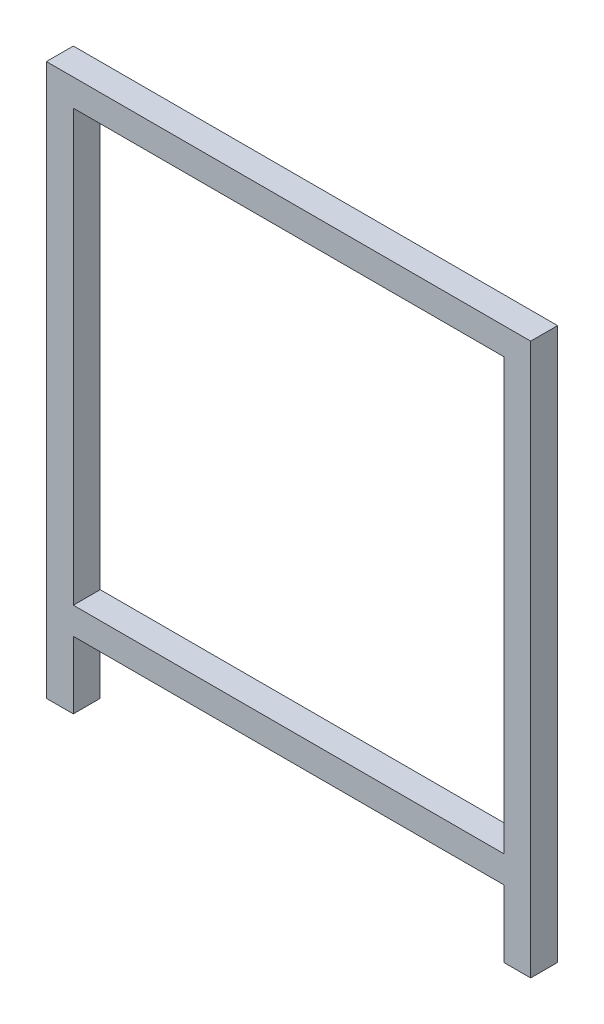
SolidWorks part; units mm, degrees
ref_plane "Front Plane" through (0, 0, 0) normal (0, 0, 1) x (1, 0, 0)
ref_plane "Top Plane" through (0, 0, 0) normal (0, 1, 0) x (1, 0, 0)
ref_plane "Right Plane" through (0, 0, 0) normal (1, 0, 0) x (0, 0, -1)
sketch "Sketch2" plane through (0, 0, 0) normal (0, 0, 1) x (1, 0, 0)
  line L0 (160, -230) -> (160, -180)
  line L1 (-180, 180) -> (180, 180)
  line L2 (-180, 180) -> (-180, -230)
  line L3 (-180, -230) -> (-160, -230)
  line L4 (180, 180) -> (180, -230)
  line L5 (160, -180) -> (-160, -180)
  line L6 (-160, -180) -> (-160, -230)
  line L7 (160, -230) -> (180, -230)
  line L8 (0, 160) -> (0, 0) construction
  line L9 (-160, 160) -> (160, 160)
  line L10 (-160, 160) -> (-160, -160)
  line L11 (-160, -160) -> (160, -160)
  line L12 (160, 160) -> (160, -160)
  line L13 (0, 0) -> (0, -160) construction
  dimension "D1" = 320
  dimension "D2" = 320
  dimension "D3" = 20
  dimension "D4" = 20
  dimension "D5" = 20
  dimension "D6" = 20
  dimension "D7" = 50
extrude "Boss-Extrude1" add sketch "Sketch2" against normal mid plane 20
